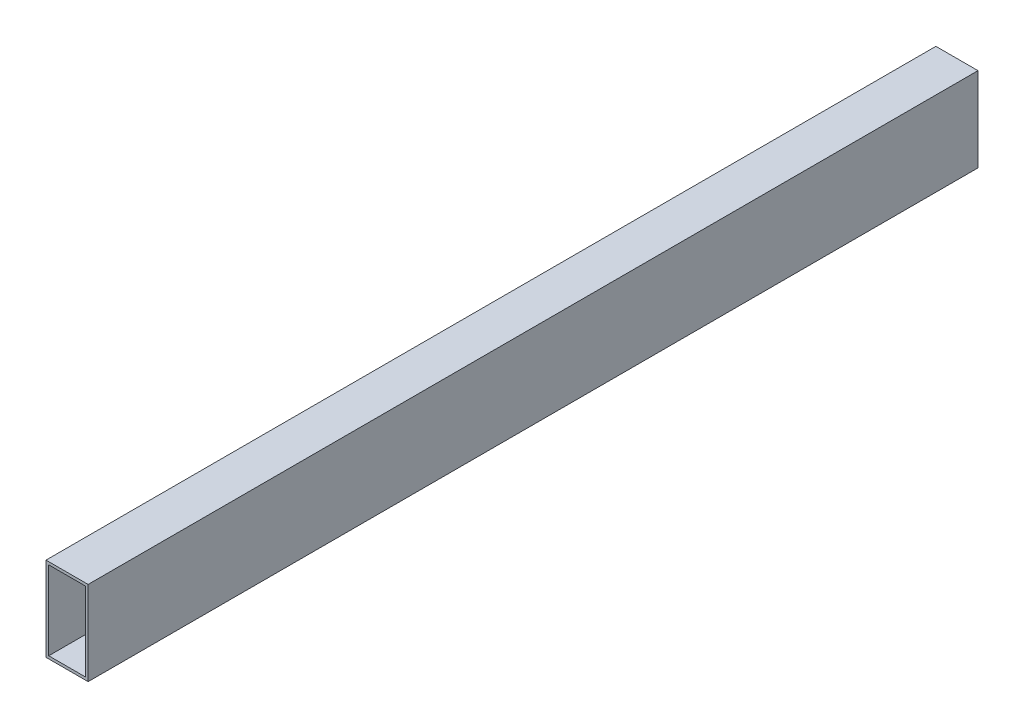
SolidWorks part; units mm, degrees
material "6061 Alloy"
ref_plane "Front Plane" through (0, 0, 0) normal (0, 0, 1) x (1, 0, 0)
ref_plane "Top Plane" through (0, 0, 0) normal (0, 1, 0) x (1, 0, 0)
ref_plane "Right Plane" through (0, 0, 0) normal (1, 0, 0) x (0, 0, -1)
sketch "Sketch1" plane through (0, 0, 0) normal (0, 0, 1) x (1, 0, 0)
  line L1 (-48.4372, -30.1994) -> (-23.0372, -30.1994)
  line L2 (-48.4372, -30.1994) -> (-48.4372, 20.6006)
  line L3 (-48.4372, 20.6006) -> (-23.0372, 20.6006)
  line L4 (-23.0372, -30.1994) -> (-23.0372, 20.6006)
  dimension "D1" = 25.4
  dimension "D2" = 50.8
extrude "Boss-Extrude1" add sketch "Sketch1" along normal blind 536.702
sketch "Sketch2" plane through (0, 0, 536.702) normal (0, 0, 1) x (1, 0, 0)
  line L0 (-48.4372, 20.6006) -> (-48.4372, -30.1994) construction
  line L1 (-46.7862, 18.9496) -> (-24.6882, 18.9496)
  line L2 (-46.7862, 18.9496) -> (-46.7862, -28.5484)
  line L3 (-46.7862, -28.5484) -> (-24.6882, -28.5484)
  line L4 (-24.6882, 18.9496) -> (-24.6882, -28.5484)
  line L5 (-46.7862, 18.9496) -> (-24.6882, -28.5484) construction
  line L6 (-46.7862, -28.5484) -> (-24.6882, 18.9496) construction
  line L7 (-23.0372, -30.1994) -> (-23.0372, 20.6006) construction
  line L8 (-23.0372, 20.6006) -> (-48.4372, 20.6006) construction
  line L9 (-48.4372, -30.1994) -> (-23.0372, -30.1994) construction
  point P0 (-35.7372, -4.7994)
  dimension "D1" = 1.651
  dimension "D2" = 1.651
  dimension "D3" = 1.651
  dimension "D4" = 1.651
extrude "Cut-Extrude1" cut sketch "Sketch2" against normal through all
